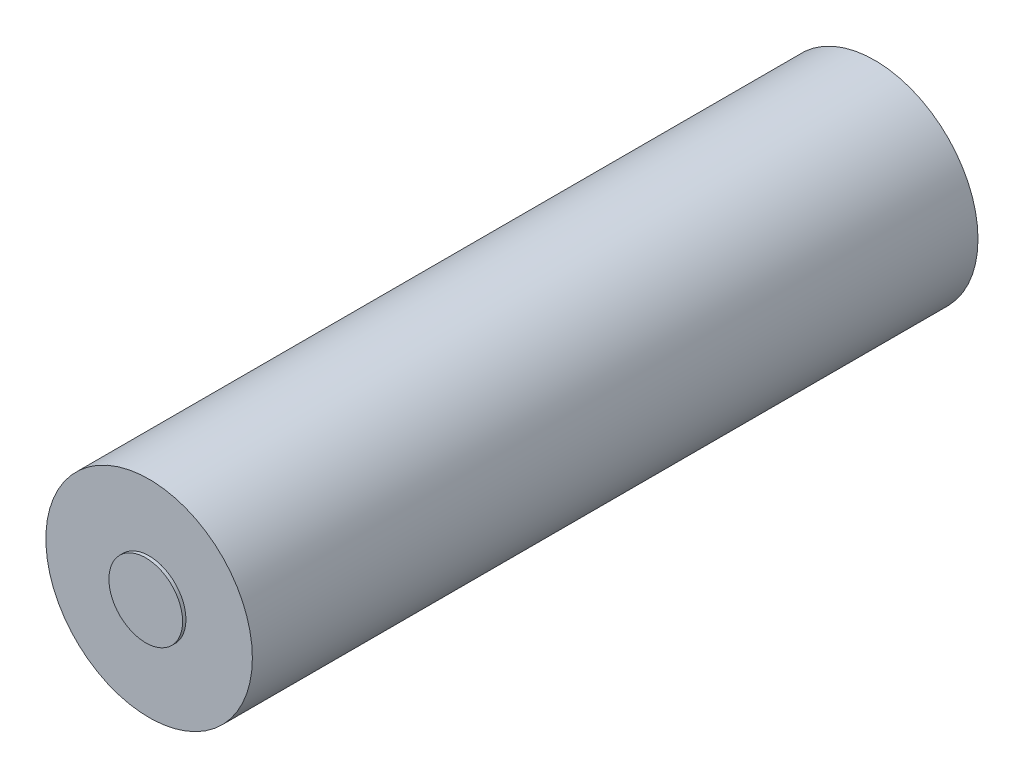
SolidWorks part; units mm, degrees
ref_plane "Front Plane" through (0, 0, 0) normal (0, 0, 1) x (1, 0, 0)
ref_plane "Top Plane" through (0, 0, 0) normal (0, 1, 0) x (1, 0, 0)
ref_plane "Right Plane" through (0, 0, 0) normal (1, 0, 0) x (0, 0, -1)
sketch "Sketch1" plane through (0, 0, 0) normal (0, 0, 1) x (1, 0, 0)
  circle A0 centre (0, 0) radius 9.25
  dimension "D1" = 18.5
extrude "Boss-Extrude1" add sketch "Sketch1" along normal blind 65
sketch "Sketch2" plane through (0, 0, 65) normal (0, 0, 1) x (1, 0, 0)
  circle A0 centre (0, 0) radius 3.3
  dimension "D1" = 6.6
extrude "Boss-Extrude2" add sketch "Sketch2" along normal blind 0.3
